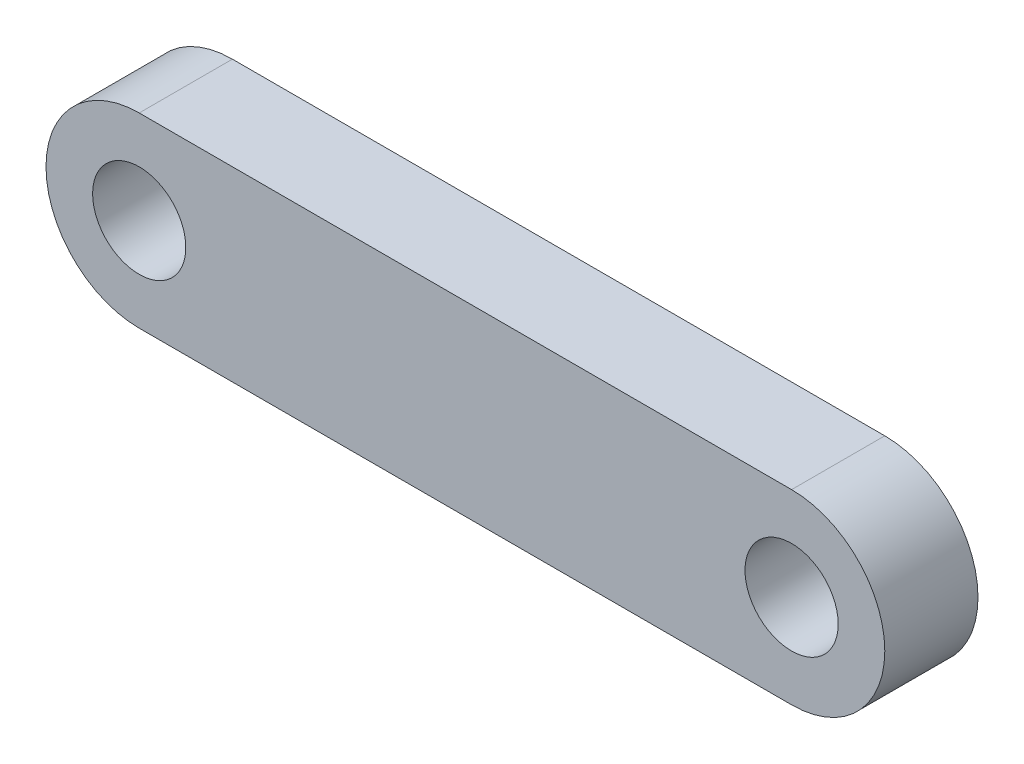
SolidWorks part; units mm, degrees
material "AISI 1035 Steel (SS)"
ref_plane "Front Plane" through (0, 0, 0) normal (0, 0, 1) x (1, 0, 0)
ref_plane "Top Plane" through (0, 0, 0) normal (0, 1, 0) x (1, 0, 0)
ref_plane "Right Plane" through (0, 0, 0) normal (1, 0, 0) x (0, 0, -1)
sketch "Sketch1" plane through (0, 0, 0) normal (0, 0, 1) x (1, 0, 0)
  line L0 (-35, 0) -> (35, 0) construction
  line L1 (-35, 10) -> (35, 10)
  line L2 (-35, -10) -> (35, -10)
  line L3 (0, 26.7615) -> (0, -38.2846) construction
  arc A0 (-35, 10) -> (-35, -10) centre (-35, 0) ccw
  arc A1 (35, -10) -> (35, 10) centre (35, 0) ccw
  circle A2 centre (35, 0) radius 5
  circle A3 centre (-35, 0) radius 5
  point P2 (0, 0)
  dimension "D3" = 10
  dimension "D1" = 70
  dimension "D2" = 20
extrude "Boss-Extrude1" add sketch "Sketch1" along normal blind 10
